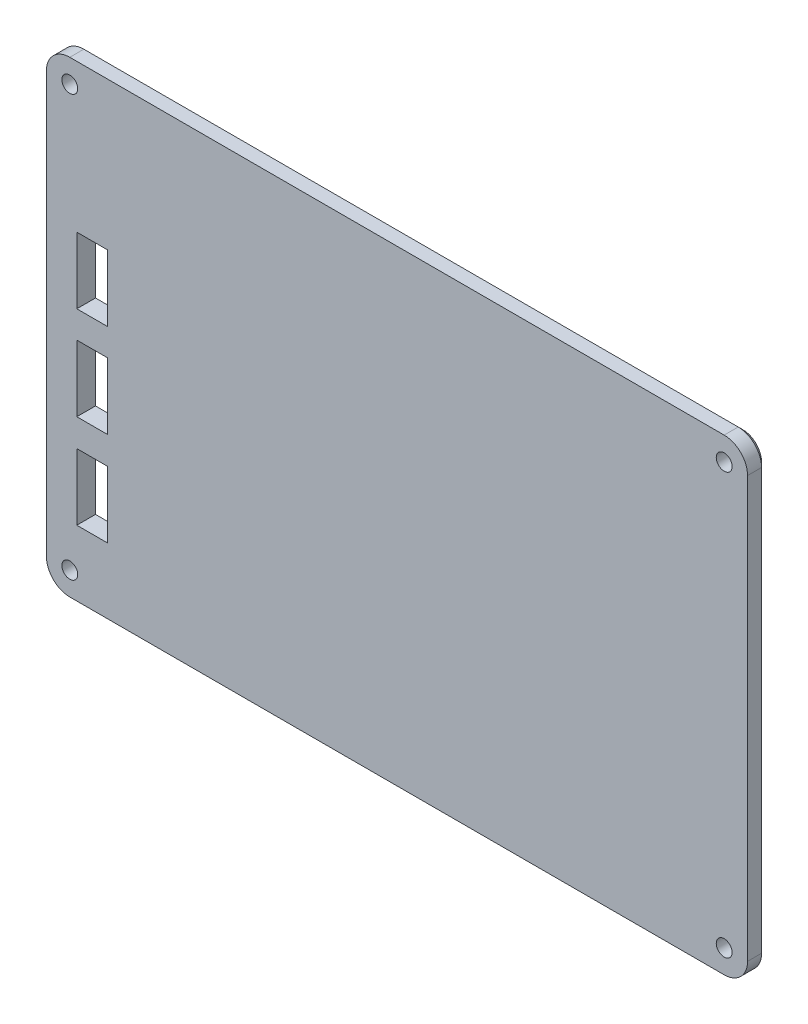
SolidWorks part; units mm, degrees
ref_plane "Přední" through (0, 0, 0) normal (0, 0, 1) x (1, 0, 0)
ref_plane "Horní" through (0, 0, 0) normal (0, 1, 0) x (1, 0, 0)
ref_plane "Pravá" through (0, 0, 0) normal (1, 0, 0) x (0, 0, -1)
sketch "Skica1" plane through (0, 0, -86) normal (0, 0, -1) x (-1, 0, 0)
  line L4 (-75, 44.35) -> (-75, -45.65)
  line L5 (-70, -50.65) -> (70, -50.65)
  line L6 (75, -45.65) -> (75, 44.35)
  line L7 (70, 49.35) -> (-70, 49.35)
  line L8 (-75, 44.35) -> (-75, -45.65)
  line L9 (-70, -50.65) -> (70, -50.65)
  line L10 (75, -45.65) -> (75, 44.35)
  line L11 (70, 49.35) -> (-70, 49.35)
  arc A4 (-75, -45.65) -> (-70, -50.65) centre (-70, -45.65) ccw
  arc A5 (70, -50.65) -> (75, -45.65) centre (70, -45.65) ccw
  arc A6 (75, 44.35) -> (70, 49.35) centre (70, 44.35) ccw
  arc A7 (-70, 49.35) -> (-75, 44.35) centre (-70, 44.35) ccw
  arc A8 (-75, -45.65) -> (-70, -50.65) centre (-70, -45.65) ccw
  arc A9 (70, -50.65) -> (75, -45.65) centre (70, -45.65) ccw
  arc A10 (75, 44.35) -> (70, 49.35) centre (70, 44.35) ccw
  arc A11 (-70, 49.35) -> (-75, 44.35) centre (-70, 44.35) ccw
  dimension "D1" = 0
extrude "Přidat vysunutím1" add sketch "Skica1" along normal blind 4
hole_wizard "Kuželové zahloubení pro M3 šroubu se zápustnou hlavou plochou1" positions "Skica3" profile "Skica2" countersink size "M3" standard "DIN" end condition up to next
sketch "Skica3" plane through (0, 0, -90) normal (0, 0, -1) x (-1, 0, 0)
  point P0 (70, -45.6578)
  point P3 (70, 44.3578)
  point P6 (-70, 44.3578)
  point P9 (-70, -45.6578)
sketch "Skica2" plane through (-70, -45.6578, -90) normal (1, 0, 0) x (0, 1, 0)
  line L0 (0, 0) -> (0, 4)
  line L1 (0, 4) -> (1.7, 4)
  line L2 (1.7, 4) -> (1.7, 1.45)
  line L3 (1.7, 1.45) -> (3.15, 0)
  line L5 (3.15, 0) -> (0, 0)
  line L6 (-1.7, 1.45) -> (-3.15, 0) construction
  line L11 (0, -6.35) -> (0, 107.95) construction
  dimension "Průměr díry skrz" = 3.4
  dimension "Hloubka díry skrz" = 4
  dimension "Průměr blíz. kuž. zahloubení" = 6.3
  dimension "Úhel blíz. kuž. zahloubení" = 90
chamfer "Zkosení1" distance 1 angle 45 8 edges at (0, -50.65, -90) (-73.5355, -49.1855, -90) (73.5355, -49.1855, -90) (-75, -0.65, -90) (75, -0.65, -90) (-73.5355, 47.8855, -90) (73.5355, 47.8855, -90) (0, 49.35, -90)
sketch "Skica4" plane through (0, 0, -90) normal (0, 0, -1) x (-1, 0, 0)
  line L0 (62.4, -36.1) -> (68, -36.1) construction
  line L1 (68, -36.1) -> (68, -22.9) construction
  line L2 (68, -22.9) -> (62.4, -22.9) construction
  line L3 (62.4, -22.9) -> (62.4, -36.1) construction
  line L4 (62.4, -16) -> (68, -16) construction
  line L5 (68, -16) -> (68, -2.8) construction
  line L6 (68, -2.8) -> (62.4, -2.8) construction
  line L7 (62.4, -2.8) -> (62.4, -16) construction
  line L8 (62.4, 4) -> (68, 4) construction
  line L9 (68, 4) -> (68, 17.2) construction
  line L10 (68, 17.2) -> (62.4, 17.2) construction
  line L11 (62.4, 17.2) -> (62.4, 4) construction
  line L12 (62.4, 24.1) -> (68, 24.1) construction
  line L13 (68, 24.1) -> (68, 37.3) construction
  line L14 (68, 37.3) -> (62.4, 37.3) construction
  line L15 (62.4, 37.3) -> (62.4, 24.1) construction
  line L16 (62.4, -36.1) -> (68, -36.1) construction
  line L17 (68, -36.1) -> (68, -22.9) construction
  line L18 (68, -22.9) -> (62.4, -22.9) construction
  line L19 (62.4, -22.9) -> (62.4, -36.1) construction
  line L20 (62.4, -16) -> (68, -16) construction
  line L21 (68, -16) -> (68, -2.8) construction
  line L22 (68, -2.8) -> (62.4, -2.8) construction
  line L23 (62.4, -2.8) -> (62.4, -16) construction
  line L24 (62.4, 4) -> (68, 4) construction
  line L25 (68, 4) -> (68, 17.2) construction
  line L26 (68, 17.2) -> (62.4, 17.2) construction
  line L27 (62.4, 17.2) -> (62.4, 4) construction
  line L28 (62.4, 24.1) -> (68, 24.1) construction
  line L29 (68, 24.1) -> (68, 37.3) construction
  line L30 (68, 37.3) -> (62.4, 37.3) construction
  line L31 (62.4, 37.3) -> (62.4, 24.1) construction
  line L32 (61.9, -22.4) -> (61.9, -36.6)
  line L33 (61.9, -36.6) -> (68.5, -36.6)
  line L34 (68.5, -36.6) -> (68.5, -22.4)
  line L35 (68.5, -22.4) -> (61.9, -22.4)
  line L36 (61.9, -16.5) -> (68.5, -16.5)
  line L37 (68.5, -16.5) -> (68.5, -2.3)
  line L38 (68.5, -2.3) -> (61.9, -2.3)
  line L39 (61.9, -2.3) -> (61.9, -16.5)
  line L40 (61.9, 3.5) -> (68.5, 3.5)
  line L41 (68.5, 3.5) -> (68.5, 17.7)
  line L42 (68.5, 17.7) -> (61.9, 17.7)
  line L43 (61.9, 17.7) -> (61.9, 3.5)
  line L44 (61.9, 23.6) -> (68.5, 23.6) construction
  line L45 (68.5, 23.6) -> (68.5, 37.8) construction
  line L46 (68.5, 37.8) -> (61.9, 37.8) construction
  line L47 (61.9, 37.8) -> (61.9, 23.6) construction
  dimension "D1" = 0.5
extrude "Odebrat vysunutím1" cut sketch "Skica4" against normal through all
